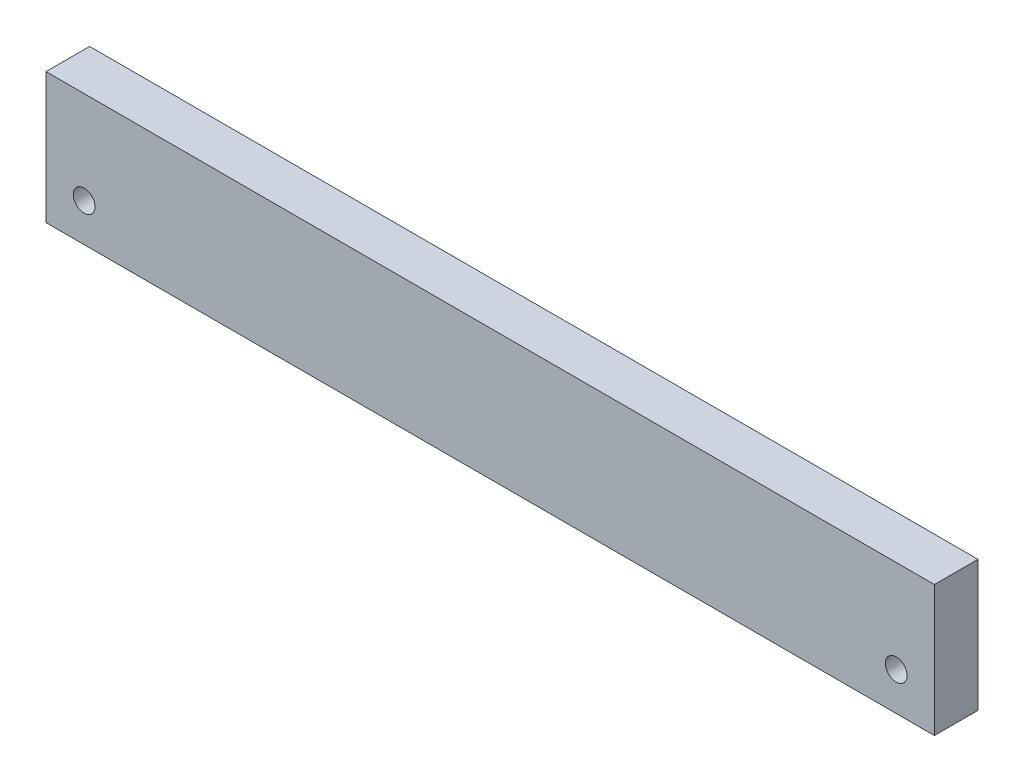
SolidWorks part; units mm, degrees
ref_plane "Front Plane" through (0, 0, 0) normal (0, 0, 1) x (1, 0, 0)
ref_plane "Top Plane" through (0, 0, 0) normal (0, 1, 0) x (1, 0, 0)
ref_plane "Right Plane" through (0, 0, 0) normal (1, 0, 0) x (0, 0, -1)
sketch "Sketch1" plane through (0, 0, 0) normal (0, 0, 1) x (1, 0, 0)
  line L0 (-40.75, -2.5) -> (40.75, -2.5) construction
  line L1 (-40.75, -6) -> (40.75, -6)
  line L2 (-40.75, -6) -> (-40.75, 6)
  line L3 (-40.75, 6) -> (40.75, 6)
  line L4 (40.75, -6) -> (40.75, 6)
  line L5 (-40.75, -6) -> (40.75, 6) construction
  line L6 (-40.75, 6) -> (40.75, -6) construction
  line L7 (0, 0) -> (0, -6) construction
  circle A0 centre (-37.25, -2.5) radius 1
  circle A1 centre (37.25, -2.5) radius 1
  point P0 (0, 0)
  dimension "D4" = 2
  dimension "D5" = 3.5
  dimension "D1" = 12
  dimension "D2" = 81.5
  dimension "D3" = 3.5
extrude "Boss-Extrude1" add sketch "Sketch1" along normal blind 4
